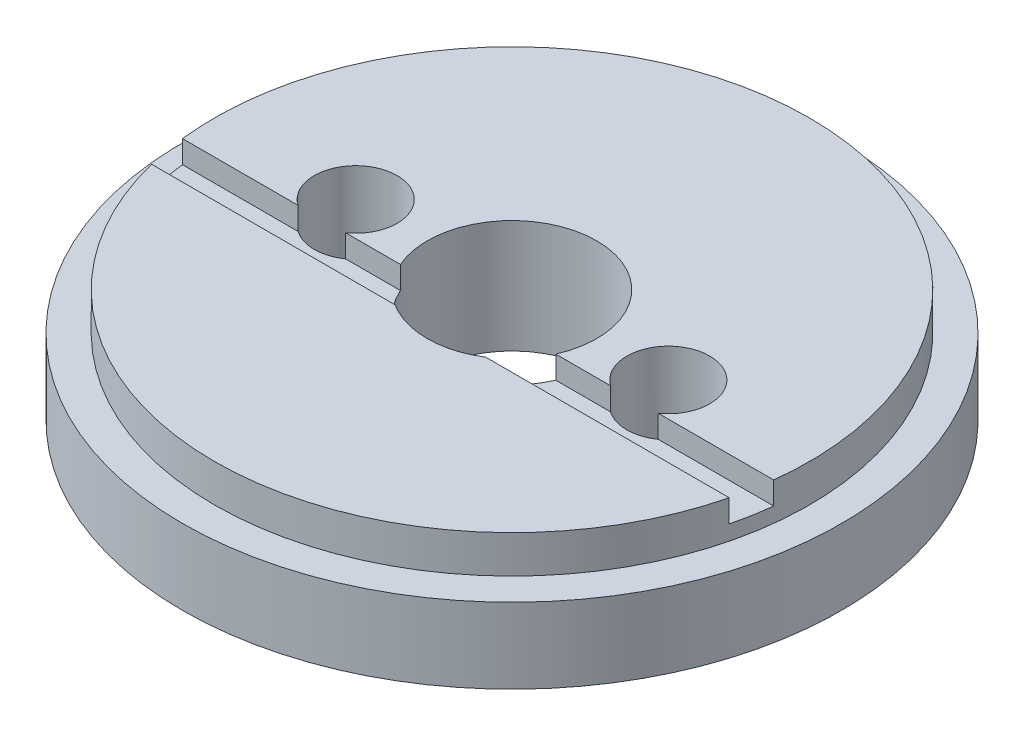
SolidWorks part; units mm, degrees
ref_plane "Front Plane" through (0, 0, 0) normal (0, 0, 1) x (1, 0, 0)
ref_plane "Top Plane" through (0, 0, 0) normal (0, 1, 0) x (1, 0, 0)
ref_plane "Right Plane" through (0, 0, 0) normal (1, 0, 0) x (0, 0, -1)
sketch "Sketch2" plane through (0, 0, 0) normal (0, 1, 0) x (1, 0, 0)
  line L0 (-4.5, 0) -> (4.5, 0) construction
  line L1 (-4.5, -3.6167) -> (-4.5, 3.6167)
  line L4 (0, 0) -> (0, 18.8683) construction
  line L6 (4.5, -3.6167) -> (4.5, 3.6167)
  circle A0 centre (0, 0) radius 17.5
  circle A1 centre (0, 0) radius 4.5
  circle A3 centre (-8.3, 0) radius 2.2
  circle A4 centre (8.3, 0) radius 2.2
  point P9 (-4.5, 0)
  dimension "D1" = 8.3
extrude "Boss-Extrude2" add sketch "Sketch2" along normal blind 6
sketch "Sketch3" plane through (0, 6, 0) normal (0, 1, 0) x (1, 0, 0)
  circle A0 centre (0, 0) radius 15.8
extrude "Cut-Extrude1" cut sketch "Sketch3" against normal blind 2 flip side to cut
sketch "Sketch4" plane through (0, 6, 0) normal (0, 1, 0) x (1, 0, 0)
  line L0 (-8.3, -2.2) -> (28.4799, -2.2) construction
  line L1 (-8.3, -1.8) -> (28.4799, -1.8) construction
  line L2 (-15.6971, -1.8) -> (15.6971, -1.8)
  line L3 (-15.6971, -3.8) -> (15.6971, -3.8)
  circle A0 centre (-8.3, 0) radius 2.2 construction
  circle A1 centre (0, 0) radius 15.8 construction
  circle A2 centre (0, 0) radius 15.8 construction
  circle M4 centre (-8.3, 0) radius 2.2
  circle M5 centre (0, 0) radius 4.5
  circle M6 centre (8.3, 0) radius 2.2
  circle M7 centre (0, 0) radius 15.8
  dimension "D1" = 0.4
  dimension "D2" = 2
extrude "Cut-Extrude3" cut sketch "Sketch4" against normal blind 1.2 contours L3 L2 M7 M5 M4 | L3 L2 M5 M7 M6
